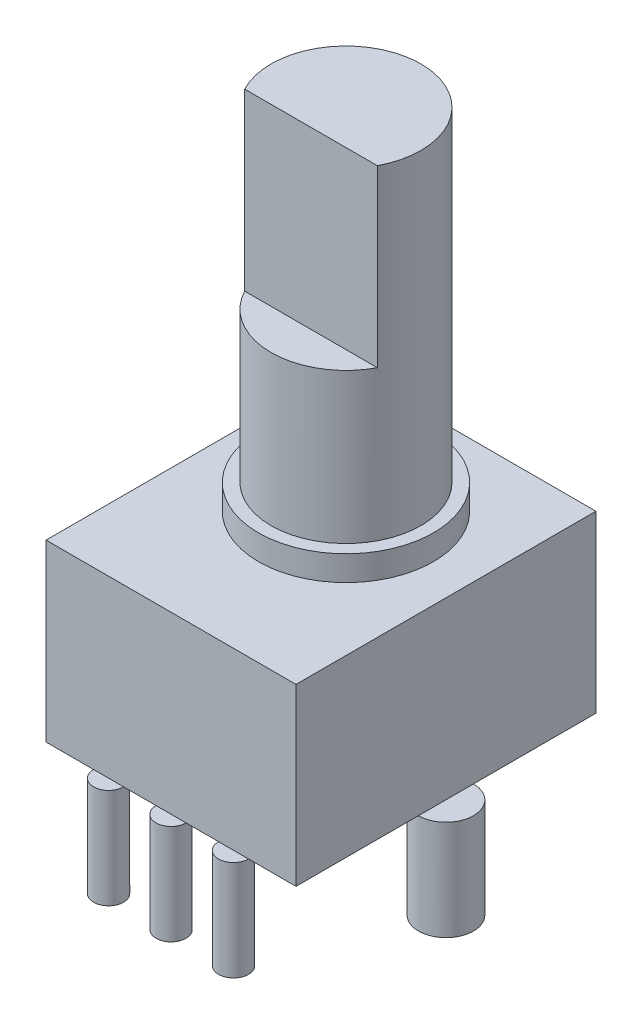
SolidWorks part; units mm, degrees
ref_plane "Front Plane" through (0, 0, 0) normal (0, 0, 1) x (1, 0, 0)
ref_plane "Top Plane" through (0, 0, 0) normal (0, 1, 0) x (1, 0, 0)
ref_plane "Right Plane" through (0, 0, 0) normal (1, 0, 0) x (0, 0, -1)
sketch "Sketch1" plane through (0, 0, 0) normal (0, 1, 0) x (1, 0, 0)
  line L1 (0, -6.93) -> (0, 6.93) construction
  line L2 (-55, 0) -> (55, 0) construction
  circle A0 centre (0, 1) radius 3
  dimension "D1" = 6
  dimension "D2" = 1
extrude "Boss-Extrude1" add sketch "Sketch1" along normal blind 6
sketch "Sketch2" plane through (0, 6, 0) normal (0, 1, 0) x (1, 0, 0)
  line L0 (-2.6533, -0.4) -> (2.6533, -0.4)
  circle A1 centre (0, 1) radius 3
  arc A2 (2.6533, -0.4) -> (-2.6533, -0.4) centre (0, 1) ccw
  dimension "D2" = 4.4
  dimension "D1" = 0
extrude "Boss-Extrude2" add sketch "Sketch2" along normal blind 7
sketch "Sketch3" plane through (0, 0, 0) normal (0, -1, 0) x (1, 0, 0)
  circle A2 centre (0, -1) radius 3.5
  circle A3 centre (0, -1) radius 3.5
  dimension "D1" = 0.5
extrude "Boss-Extrude3" add sketch "Sketch3" along normal blind 1
sketch "Sketch4" plane through (0, -1, 0) normal (0, -1, 0) x (1, 0, 0)
  line L0 (-5, -6) -> (5, 6) construction
  line L1 (-5, -6) -> (5, -6)
  line L2 (-5, -6) -> (-5, 6)
  line L3 (-5, 6) -> (5, 6)
  line L4 (5, -6) -> (5, 6)
  dimension "D1" = 10
  dimension "D2" = 12
extrude "Boss-Extrude4" add sketch "Sketch4" along normal blind 7
sketch "Sketch5" plane through (0, -8, 0) normal (0, -1, 0) x (1, 0, 0)
  line L0 (55, 0) -> (-55, 0) construction
  line L1 (5, -6) -> (5, 6) construction
  circle A0 centre (-5.0012, 0) radius 1.1
  circle A1 centre (5, 0) radius 1.1
  dimension "D1" = 2.2
  dimension "D2" = 10.0012
extrude "Boss-Extrude5" add sketch "Sketch5" along normal blind 4
sketch "Sketch6" plane through (0, -8, 0) normal (0, -1, 0) x (1, 0, 0)
  line L0 (5, 6) -> (-5, 6) construction
  line L1 (-2.5, 6) -> (0, 6) construction
  line L2 (0, 6) -> (2.5, 6) construction
  circle A0 centre (0, 6) radius 0.6
  circle A1 centre (2.5, 6) radius 0.6
  circle A2 centre (-2.5, 6) radius 0.6
  dimension "D1" = 1.2
  dimension "D2" = 2.5
extrude "Boss-Extrude6" add sketch "Sketch6" along normal blind 4
